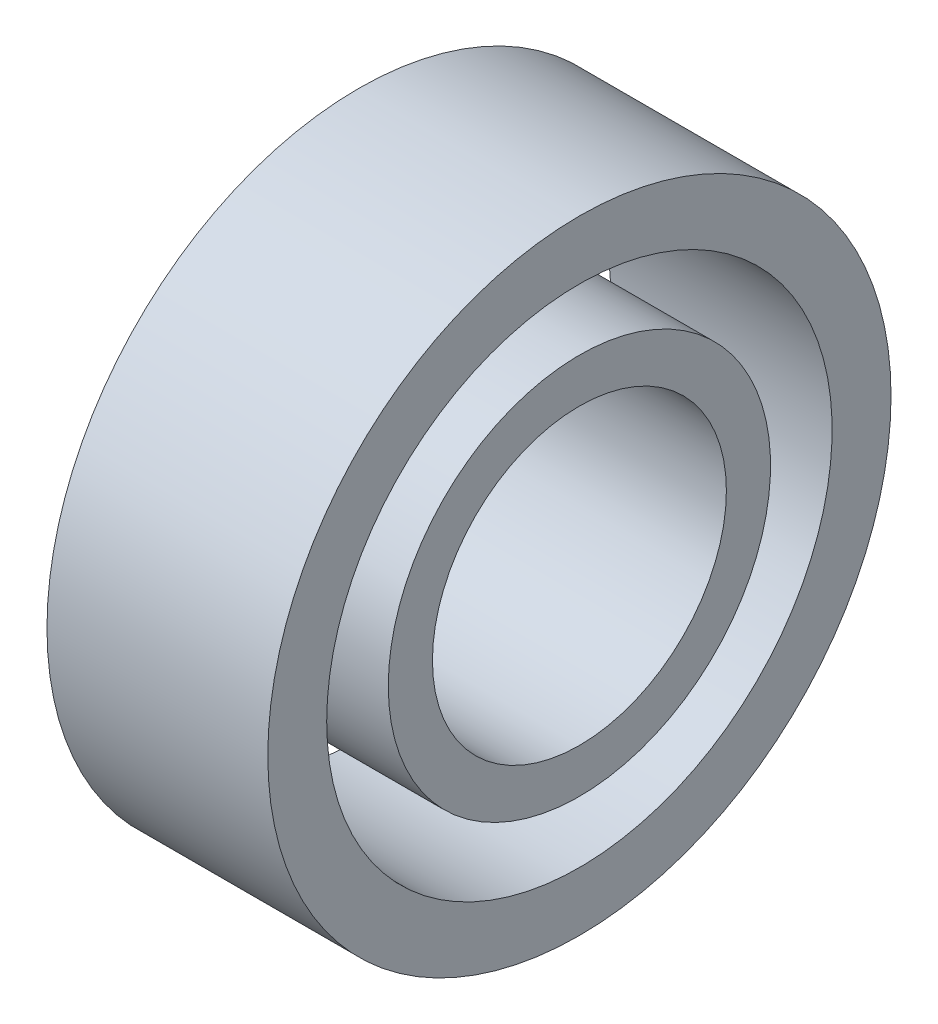
SolidWorks part; units mm, degrees
ref_plane "Front Plane" through (0, 0, 0) normal (0, 0, 1) x (1, 0, 0)
ref_plane "Top Plane" through (0, 0, 0) normal (0, 1, 0) x (1, 0, 0)
ref_plane "Right Plane" through (0, 0, 0) normal (1, 0, 0) x (0, 0, -1)
sketch "Sketch2" plane through (0, 0, 0) normal (0, 0, 1) x (1, 0, 0)
  line L0 (0, 9.9907) -> (0, -12.6977) construction
  line L1 (-11.7209, 0) -> (16.7442, 0) construction
  line L2 (-2.25, 6.35) -> (2.25, 6.35)
  line L3 (-2.25, 6.35) -> (-2.25, 5.15)
  line L4 (-2.25, 5.15) -> (2.25, 5.15)
  line L5 (2.25, 6.35) -> (2.25, 5.15)
  line L6 (-2.25, 3.895) -> (2.25, 3.895)
  line L7 (-2.25, 3.895) -> (-2.25, 2.995)
  line L8 (-2.25, 2.995) -> (2.25, 2.995)
  line L9 (2.25, 3.895) -> (2.25, 2.995)
  dimension "D1" = 1.2
  dimension "D2" = 4.5
  dimension "D3" = 6.35
  dimension "D4" = 0.9
  dimension "D5" = 3.895
revolve "Revolve1" add sketch "Sketch2" angle 360 about L1
